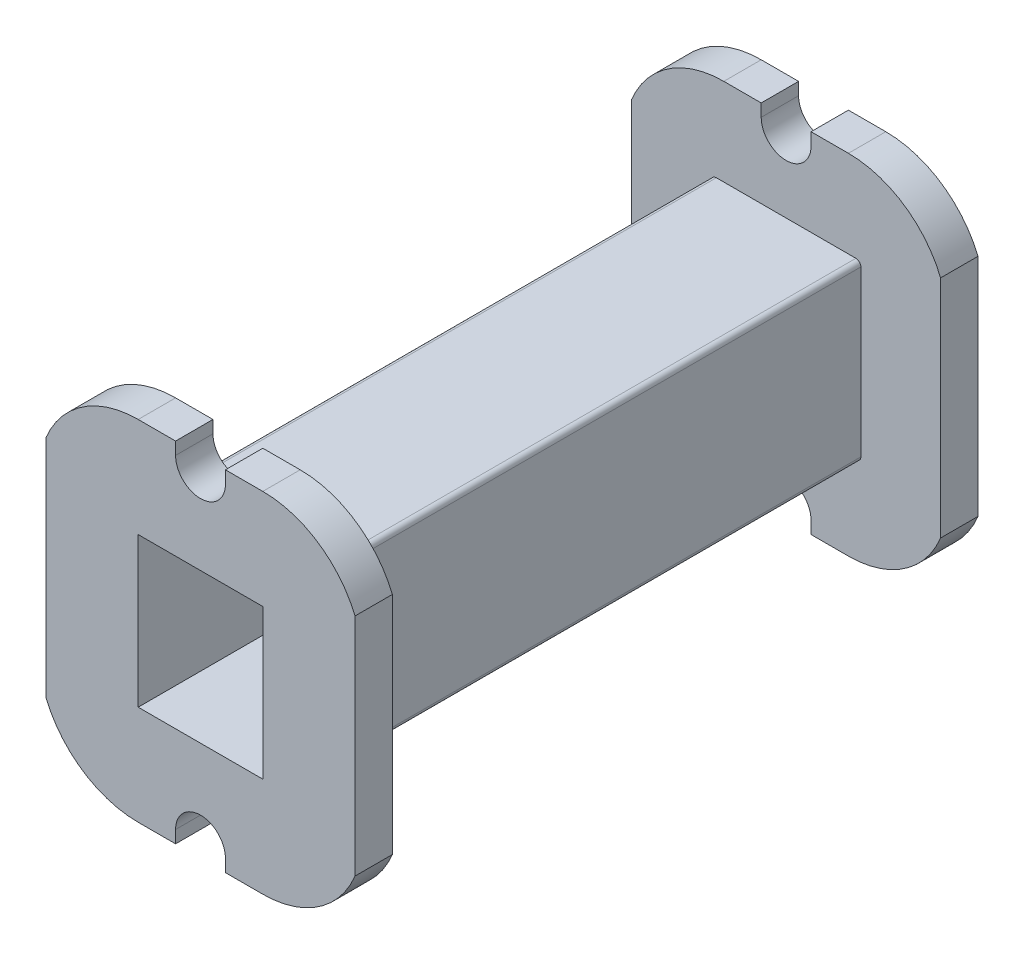
SolidWorks part; units mm, degrees
ref_plane "前视基准面" through (0, 0, 0) normal (0, 0, 1) x (1, 0, 0)
ref_plane "上视基准面" through (0, 0, 0) normal (0, 1, 0) x (1, 0, 0)
ref_plane "右视基准面" through (0, 0, 0) normal (1, 0, 0) x (0, 0, -1)
sketch "草图1" plane through (0, 0, 0) normal (0, 0, 1) x (1, 0, 0)
  line L0 (-3, 3.5) -> (3, 3.5)
  line L1 (-2.5, 3) -> (2.5, 3)
  line L2 (-2.5, 3) -> (-2.5, -3)
  line L3 (-2.5, -3) -> (2.5, -3)
  line L4 (2.5, 3) -> (2.5, -3)
  line L5 (-2.5, 3) -> (2.5, -3) construction
  line L6 (-2.5, -3) -> (2.5, 3) construction
  line L7 (3, 3.5) -> (3, -3.5)
  line L8 (-3, -3.5) -> (3, -3.5)
  line L9 (-3, 3.5) -> (-3, -3.5)
  point P0 (0, 0)
  dimension "D1" = 5
  dimension "D2" = 6
  dimension "D3" = 0.5
extrude "凸台-拉伸1" add sketch "草图1" along normal mid plane 25
sketch "草图2" plane through (0, 0, 12.5) normal (0, 0, 1) x (1, 0, 0)
  line L1 (-3, -3.5) -> (3, -3.5)
  line L2 (-3, -3.5) -> (-3, 3.5)
  line L3 (-3, 3.5) -> (3, 3.5)
  line L4 (3, -3.5) -> (3, 3.5)
  line L5 (-3, -3.5) -> (3, 3.5) construction
  line L6 (-3, 3.5) -> (3, -3.5) construction
  line L7 (-6.5, -10.75) -> (6.5, -10.75)
  line L8 (-6.5, -10.75) -> (-6.5, 10.75)
  line L9 (-6.5, 10.75) -> (6.5, 10.75)
  line L10 (6.5, -10.75) -> (6.5, 10.75)
  line L11 (-6.5, -10.75) -> (6.5, 10.75) construction
  line L12 (-6.5, 10.75) -> (6.5, -10.75) construction
  circle A0 centre (0, 0) radius 9.5
  point P0 (0, 0)
  point P7 (0, 0)
  line M3 (-3, 3.5) -> (-3, -3.5)
  line M4 (-3, -3.5) -> (3, -3.5)
  line M5 (3, -3.5) -> (3, 3.5)
  line M6 (3, 3.5) -> (-3, 3.5)
  dimension "D3" = 19
  dimension "D1" = 13
  dimension "D2" = 21.5
extrude "凸台-拉伸2" add sketch "草图2" against normal blind 1.5 contours L10 A0 L8 M3 M6 M5 M4
mirror "镜向1" about plane through (0, 0, 0) normal (0, 0, 1) of "凸台-拉伸2"
sketch "草图3" plane through (0, 0, 12.5) normal (0, 0, 1) x (1, 0, 0)
  line L1 (-9.3579, 7) -> (9.3579, 7)
  line L2 (-9.3579, 7) -> (-9.3579, -7)
  line L3 (-9.3579, -7) -> (9.3579, -7)
  line L4 (9.3579, 7) -> (9.3579, -7)
  line L5 (-9.3579, 7) -> (9.3579, -7) construction
  line L6 (-9.3579, -7) -> (9.3579, 7) construction
  circle A0 centre (0, 0) radius 19.1004
  point P0 (0, 0)
  dimension "D1" = 14
extrude "切除-拉伸1" cut sketch "草图3" against normal through all
sketch "草图4" plane through (0, 0, 12.5) normal (0, 0, 1) x (1, 0, 0)
  line L4 (-6.4226, -7) -> (6.4226, -7)
  line L5 (6.5, -6.9282) -> (6.5, 6.9282)
  line L6 (6.4226, 7) -> (-6.4226, 7)
  line L7 (-6.5, 6.9282) -> (-6.5, -6.9282)
  line L8 (-6.4226, -7) -> (6.4226, -7)
  line L9 (6.5, -6.9282) -> (6.5, 6.9282)
  line L10 (6.4226, 7) -> (-6.4226, 7)
  line L11 (-6.5, 6.9282) -> (-6.5, -6.9282)
  circle A0 centre (-2.5, 3) radius 4
  circle A1 centre (2.5, 3) radius 4
  circle A2 centre (2.5, -3) radius 4
  circle A3 centre (-2.5, -3) radius 4
  arc A8 (-6.5, -6.9282) -> (-6.4226, -7) centre (0, 0) ccw
  arc A9 (6.4226, -7) -> (6.5, -6.9282) centre (0, 0) ccw
  arc A10 (6.5, 6.9282) -> (6.4226, 7) centre (0, 0) ccw
  arc A11 (-6.4226, 7) -> (-6.5, 6.9282) centre (0, 0) ccw
  arc A12 (-6.5, -6.9282) -> (-6.4226, -7) centre (0, 0) ccw
  arc A13 (6.4226, -7) -> (6.5, -6.9282) centre (0, 0) ccw
  arc A14 (6.5, 6.9282) -> (6.4226, 7) centre (0, 0) ccw
  arc A15 (-6.4226, 7) -> (-6.5, 6.9282) centre (0, 0) ccw
  arc M17 (-6.5, -6.9282) -> (-6.4226, -7) centre (0, 0) ccw
  line M18 (-6.4226, -7) -> (6.4226, -7)
  arc M19 (6.4226, -7) -> (6.5, -6.9282) centre (0, 0) ccw
  line M20 (6.5, -6.9282) -> (6.5, 6.9282)
  arc M21 (6.5, 6.9282) -> (6.4226, 7) centre (0, 0) ccw
  line M22 (6.4226, 7) -> (-6.4226, 7)
  arc M23 (-6.4226, 7) -> (-6.5, 6.9282) centre (0, 0) ccw
  line M24 (-6.5, 6.9282) -> (-6.5, -6.9282)
  dimension "D1" = 0
extrude "切除-拉伸2" cut sketch "草图4" against normal through all contours A0 L10 M23 M24 | A1 L9 M21 M22 | A2 L8 M19 M20 | A3 M24 M17 M18
sketch "草图5" plane through (0, 0, 12.5) normal (0, 0, 1) x (1, 0, 0)
  line L0 (0, 7.5) -> (0, 6.5) construction
  line L1 (-6.2, 12.6435) -> (6.2, 12.6435)
  line L2 (-6.2, 12.6435) -> (-6.2, -12.6435)
  line L3 (-6.2, -12.6435) -> (6.2, -12.6435)
  line L4 (6.2, 12.6435) -> (6.2, -12.6435)
  line L5 (-6.2, 12.6435) -> (6.2, -12.6435) construction
  line L6 (-6.2, -12.6435) -> (6.2, 12.6435) construction
  line L7 (2.5, 7) -> (-2.5, 7) construction
  line L8 (1, 7.5) -> (1, 6.5)
  line L9 (-1, 7.5) -> (-1, 6.5)
  line L10 (0, -6.5) -> (0, -7.5) construction
  line L11 (-2.5, -7) -> (2.5, -7) construction
  line L12 (1, -6.5) -> (1, -7.5)
  line L13 (-1, -6.5) -> (-1, -7.5)
  line L14 (6.5, -3) -> (6.5, 3) construction
  line L16 (-13.2201, 15.7714) -> (13.2201, 15.7714)
  line L17 (-13.2201, 15.7714) -> (-13.2201, -15.7714)
  line L18 (-13.2201, -15.7714) -> (13.2201, -15.7714)
  line L19 (13.2201, 15.7714) -> (13.2201, -15.7714)
  line L20 (-13.2201, 15.7714) -> (13.2201, -15.7714) construction
  line L21 (-13.2201, -15.7714) -> (13.2201, 15.7714) construction
  arc A0 (1, 7.5) -> (-1, 7.5) centre (0, 7.5) ccw
  arc A1 (-1, 6.5) -> (1, 6.5) centre (0, 6.5) ccw
  arc A2 (1, -6.5) -> (-1, -6.5) centre (0, -6.5) ccw
  arc A3 (-1, -7.5) -> (1, -7.5) centre (0, -7.5) ccw
  point P0 (0, 0)
  point P10 (0, 7)
  point P16 (0, -7)
  point P26 (0, 0)
  line M11 (-6.5, 3) -> (-6.5, -3)
  arc M12 (-6.5, -3) -> (-2.5, -7) centre (-2.5, -3) ccw
  line M13 (-2.5, -7) -> (2.5, -7)
  arc M14 (2.5, -7) -> (6.5, -3) centre (2.5, -3) ccw
  line M15 (6.5, -3) -> (6.5, 3)
  arc M16 (6.5, 3) -> (2.5, 7) centre (2.5, 3) ccw
  line M17 (2.5, 7) -> (-2.5, 7)
  arc M18 (-2.5, 7) -> (-6.5, 3) centre (-2.5, 3) ccw
  dimension "D1" = 1
  dimension "D2" = 1
  dimension "D3" = 1
  dimension "D4" = 1
  dimension "D5" = 0.3
extrude "切除-拉伸3" cut sketch "草图5" against normal through all both and the other way through all contours L9 A1 L8 M17 | L12 A2 L13 M13 | L2 M18 M11 M12 | L4 M16 M14 M15
fillet "圆角1" radius 0.2 4 edges at (3, 3.5, 0) (-3, -3.5, 0) (-3, 3.5, 0) (3, -3.5, 0)
